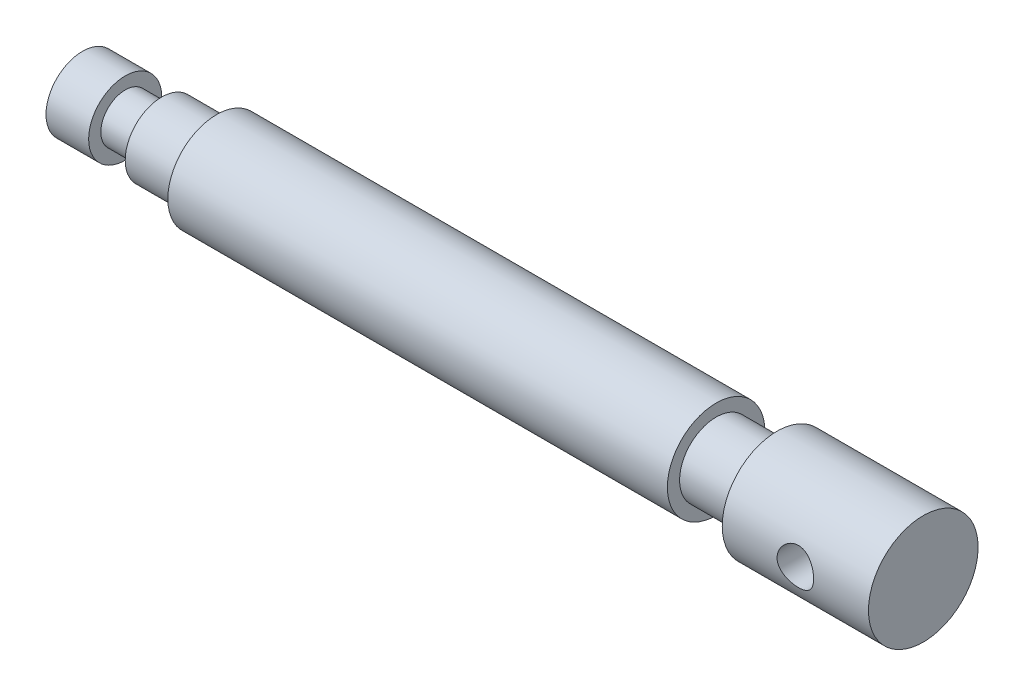
SolidWorks part; units mm, degrees
ref_plane "Front Plane" through (0, 0, 0) normal (0, 0, 1) x (1, 0, 0)
ref_plane "Top Plane" through (0, 0, 0) normal (0, 1, 0) x (1, 0, 0)
ref_plane "Right Plane" through (0, 0, 0) normal (1, 0, 0) x (0, 0, -1)
sketch "Sketch1" plane through (0, 0, 0) normal (0, 0, 1) x (1, 0, 0)
  line L0 (0, 0) -> (372.2092, 0) construction
  line L1 (0, 0) -> (0, 6)
  line L2 (0, 6) -> (7, 6)
  line L3 (7, 6) -> (7, 4)
  line L4 (7, 4) -> (13, 4)
  line L5 (13, 4) -> (13, 6)
  line L6 (13, 6) -> (22, 6)
  line L7 (22, 6) -> (22, 8)
  line L8 (22, 8) -> (104, 8)
  line L9 (104, 8) -> (104, 6)
  line L10 (104, 6) -> (114, 6)
  line L11 (114, 6) -> (114, 9)
  line L12 (114, 9) -> (138, 9)
  line L13 (138, 9) -> (138, 0)
  line L14 (0, 0) -> (138, 0)
  dimension "D1" = 138
  dimension "D2" = 24
  dimension "D3" = 10
  dimension "D4" = 82
  dimension "D5" = 7
  dimension "D6" = 6
  dimension "D7" = 4
  dimension "D8" = 6
  dimension "D9" = 8
  dimension "D10" = 9
revolve "Revolve1" add sketch "Sketch1" angle 360 about L0
sketch "Sketch2" plane through (0, 0, 0) normal (0, 0, 1) x (1, 0, 0)
  line L0 (138, -9) -> (138, 9) construction
  circle A0 centre (126, 0) radius 3
  dimension "D1" = 6
  dimension "D2" = 12
extrude "Cut-Extrude1" cut sketch "Sketch2" against normal mid plane 60
